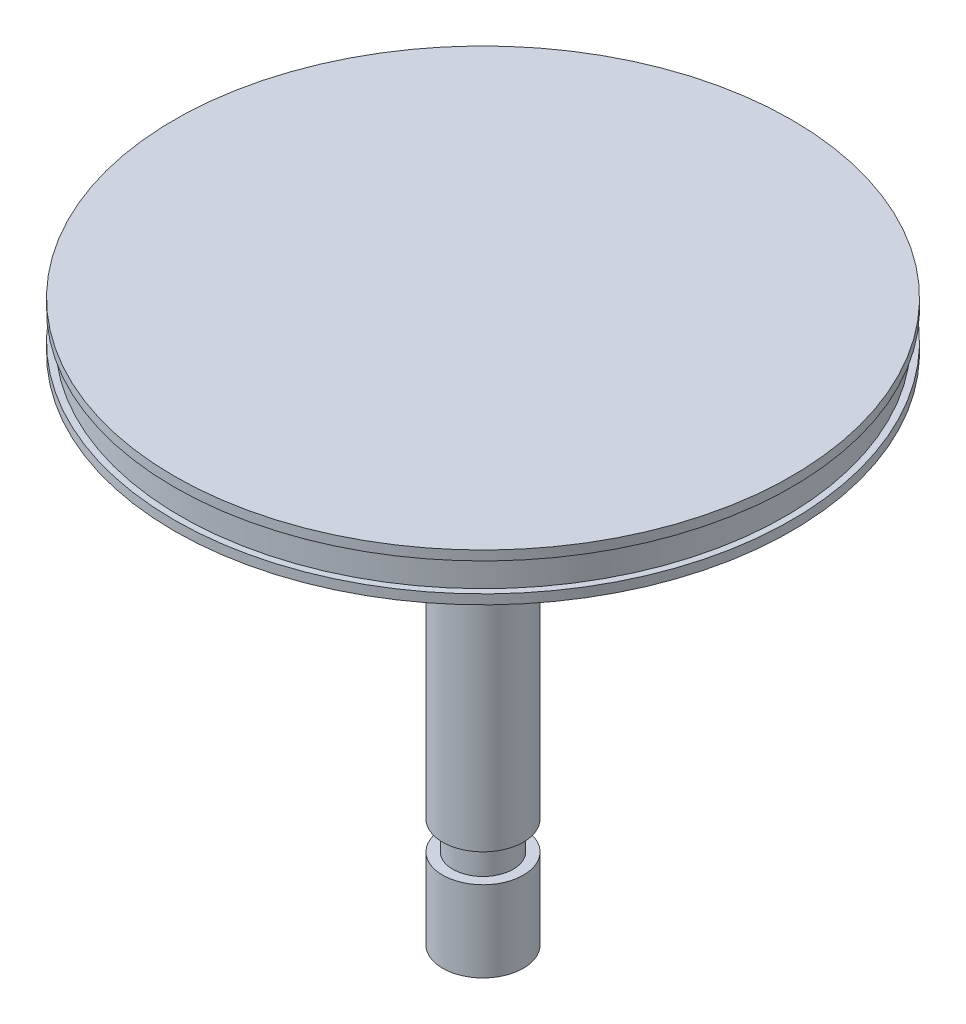
SolidWorks part; units mm, degrees
ref_plane "Front Plane" through (0, 0, 0) normal (0, 0, 1) x (1, 0, 0)
ref_plane "Top Plane" through (0, 0, 0) normal (0, 1, 0) x (1, 0, 0)
ref_plane "Right Plane" through (0, 0, 0) normal (1, 0, 0) x (0, 0, -1)
sketch "Sketch2" plane through (0, 0, 0) normal (0, 1, 0) x (1, 0, 0)
  circle A0 centre (0, 0) radius 63.66
  dimension "D1" = 127.32
extrude "Boss-Extrude1" add sketch "Sketch2" along normal mid plane 10
sketch "Sketch3" plane through (0, -5, 0) normal (0, -1, 0) x (1, 0, 0)
  circle A0 centre (0, 0) radius 65
  dimension "D1" = 130
extrude "Boss-Extrude2" add sketch "Sketch3" against normal blind 2
mirror "Mirror1" about plane through (0, 0, 0) normal (0, 1, 0) of "Boss-Extrude2"
sketch "Sketch4" plane through (0, -5, 0) normal (0, -1, 0) x (1, 0, 0)
  circle A0 centre (0, 0) radius 6.366
  dimension "D1" = 12.732
extrude "Boss-Extrude3" add sketch "Sketch4" along normal blind 108
sketch "Sketch5" plane through (0, -113, 0) normal (0, -1, 0) x (1, 0, 0)
  circle A0 centre (0, 0) radius 8.5
  dimension "D1" = 17
extrude "Boss-Extrude4" add sketch "Sketch5" against normal blind 17
sketch "Sketch6" plane through (0, -5, 0) normal (0, -1, 0) x (1, 0, 0)
  circle A0 centre (0, 0) radius 10
  dimension "D1" = 20
extrude "Boss-Extrude5" add sketch "Sketch6" along normal blind 2
sketch "Sketch7" plane through (0, -7, 0) normal (0, -1, 0) x (1, 0, 0)
  circle A0 centre (0, 0) radius 8.5
  dimension "D1" = 17
extrude "Boss-Extrude6" add sketch "Sketch7" along normal blind 17
ref_plane "Plane1" through (0, -60, 0) normal (0, -1, 0) x (-1, 0, 0)
sketch "Sketch8" plane through (0, -60, 0) normal (0, -1, 0) x (-1, 0, 0)
  circle A0 centre (0, 0) radius 8.5
  dimension "D1" = 17
extrude "Boss-Extrude7" add sketch "Sketch8" along normal mid plane 60
